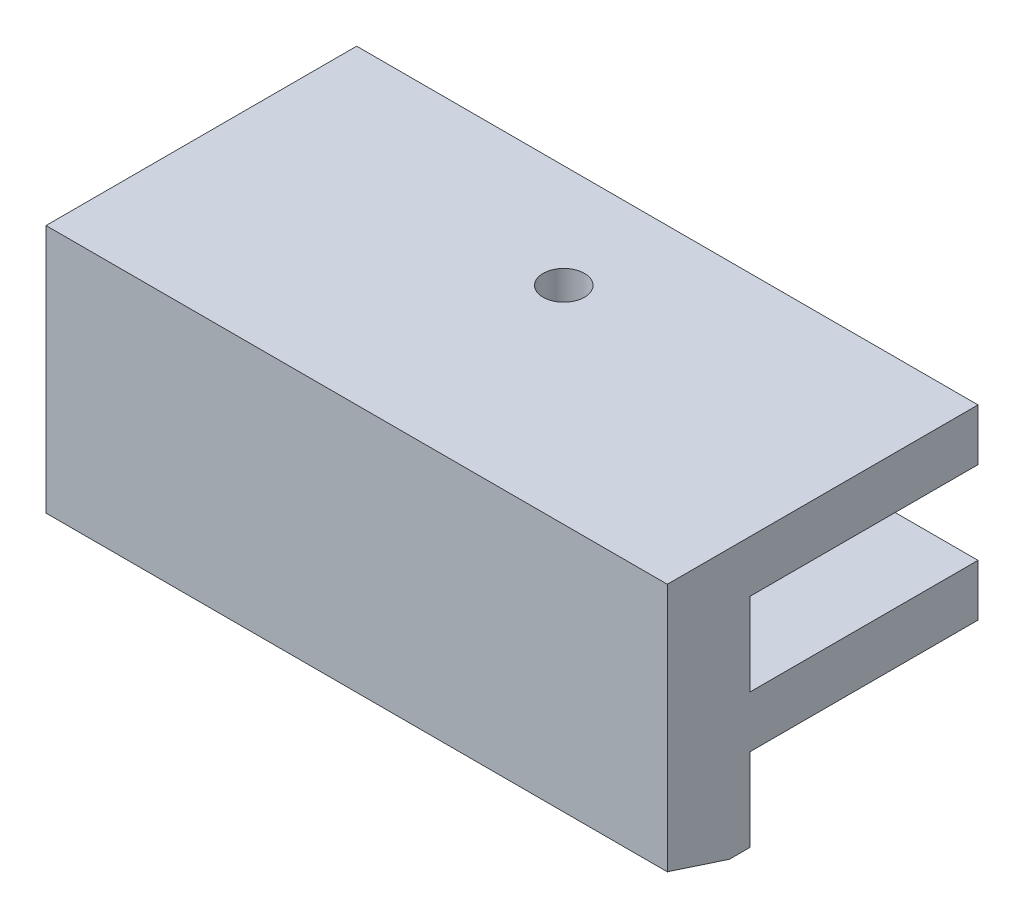
SolidWorks part; units mm, degrees
ref_plane "Płaszczyzna przednia" through (0, 0, 0) normal (0, 0, 1) x (1, 0, 0)
ref_plane "Płaszczyzna górna" through (0, 0, 0) normal (0, 1, 0) x (1, 0, 0)
ref_plane "Płaszczyzna prawa" through (0, 0, 0) normal (1, 0, 0) x (0, 0, -1)
sketch "Szkic2" plane through (0, 0, 0) normal (0, 1, 0) x (1, 0, 0)
  line L1 (-15, 7.5) -> (15, 7.5)
  line L2 (-15, 7.5) -> (-15, -7.5)
  line L3 (-15, -7.5) -> (15, -7.5)
  line L4 (15, 7.5) -> (15, -7.5)
  line L5 (-15, 7.5) -> (15, -7.5) construction
  line L6 (-15, -7.5) -> (15, 7.5) construction
  circle A0 centre (0, 2.5) radius 1
  point P0 (0, 0)
  point P9 (0, 7.5)
  dimension "D3" = 2
  dimension "D1" = 15
  dimension "D2" = 30
  dimension "D4" = 5
extrude "Dodanie-wyciągnięcie1" add sketch "Szkic2" along normal blind 2.5
ref_plane "Płaszczyzna1" through (0, 4.5, 0) normal (0, 1, 0) x (1, 0, 0)
sketch "Szkic4" plane through (0, 2.5, 0) normal (0, 1, 0) x (1, 0, 0)
  line L0 (15, -7.5) -> (15, 7.5) construction
  line L1 (-15, -7.5) -> (15, -7.5)
  line L2 (-15, -7.5) -> (-15, -3.5)
  line L3 (-15, -3.5) -> (15, -3.5)
  line L4 (15, -7.5) -> (15, -3.5)
  dimension "D1" = 4
extrude "Dodanie-wyciągnięcie2" add sketch "Szkic4" along normal blind 4 and the other way blind 6.5
mirror "Lustro3" about plane through (0, 4.5, 0) normal (0, 1, 0) of "Dodanie-wyciągnięcie1"
chamfer "Sfazowanie1" distance 3 angle 18 1 edges at (0, -4, 7.5)
